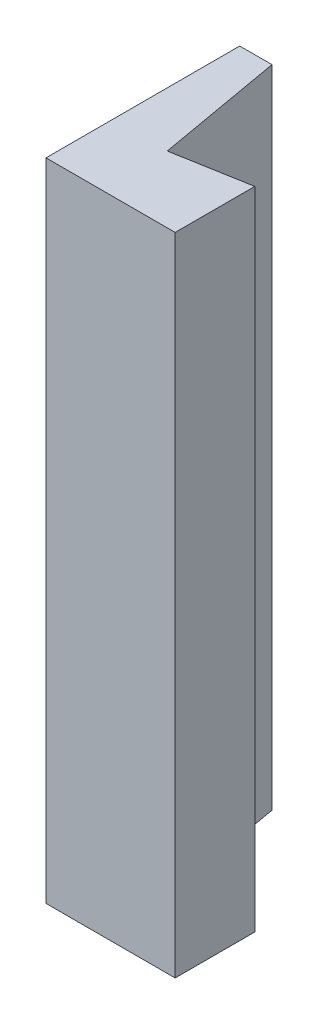
SolidWorks part; units mm, degrees
ref_plane "Front Plane" through (0, 0, 0) normal (0, 0, 1) x (1, 0, 0)
ref_plane "Top Plane" through (0, 0, 0) normal (0, 1, 0) x (1, 0, 0)
ref_plane "Right Plane" through (0, 0, 0) normal (1, 0, 0) x (0, 0, -1)
sketch "Sketch1" plane through (0, 0, 0) normal (0, 1, 0) x (1, 0, 0)
  line L0 (-6.35, 19.05) -> (-1.9393, -5.9641)
  line L1 (-12.7, -19.05) -> (12.7, -19.05)
  line L2 (-12.7, -19.05) -> (-12.7, 19.05)
  line L3 (-12.7, 19.05) -> (-6.35, 19.05)
  line L4 (12.7, -19.05) -> (12.7, -3.3828)
  line L5 (-12.7, -19.05) -> (12.7, 19.05) construction
  line L6 (-12.7, 19.05) -> (12.7, -19.05) construction
  line L7 (-1.9393, -5.9641) -> (12.7, -3.3828)
  point P0 (0, 0)
  dimension "D1" = 6.35
  dimension "D2" = 100
  dimension "D3" = 90
extrude "Boss-Extrude1" add sketch "Sketch1" along normal blind 127
